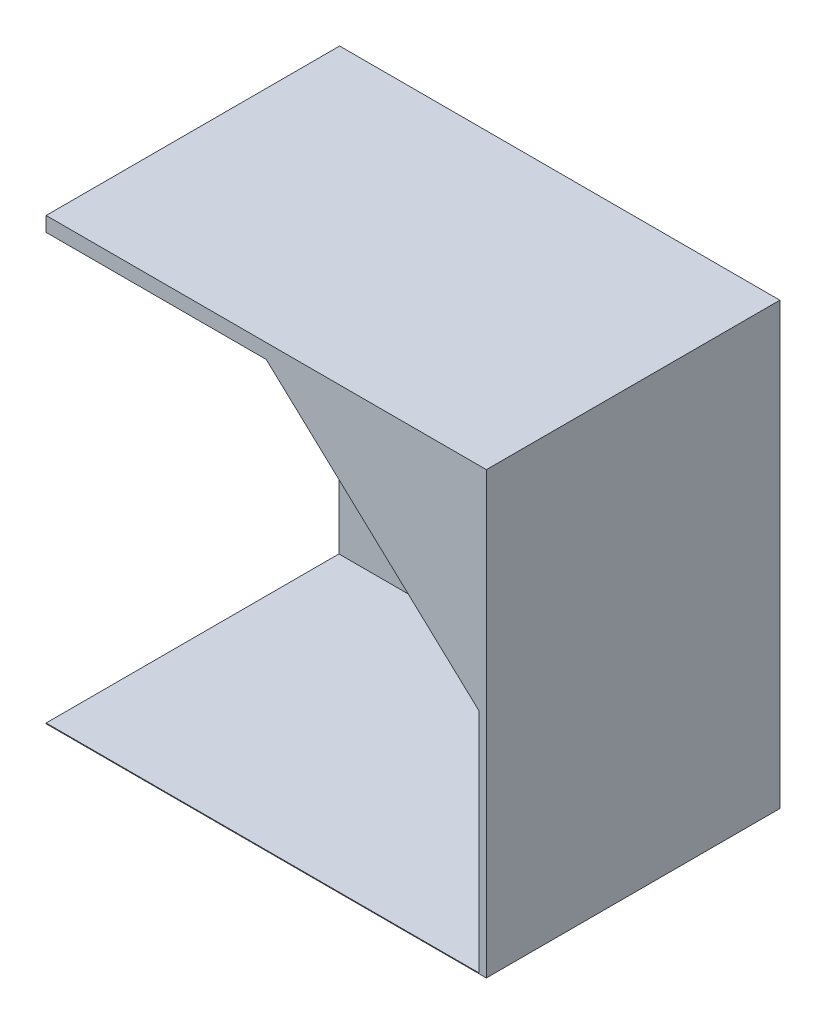
SolidWorks part; units mm, degrees
ref_plane "Front Plane" through (0, 0, 0) normal (0, 0, 1) x (1, 0, 0)
ref_plane "Top Plane" through (0, 0, 0) normal (0, 1, 0) x (1, 0, 0)
ref_plane "Right Plane" through (0, 0, 0) normal (1, 0, 0) x (0, 0, -1)
sketch "Sketch1" plane through (0, 0, 0) normal (0, 0, 1) x (1, 0, 0)
  line L0 (-1599.1508, 0) -> (1757.5573, 0) construction
  line L1 (0, 899.5223) -> (0, -922.1518) construction
  line L3 (1500, -1500) -> (-1500, -1500)
  line L4 (1500, -1500) -> (1500, 1500)
  line L5 (1500, 1500) -> (-1500, 1500)
  line L6 (-1500, -1500) -> (-1500, 1500)
  line L7 (1500, -1500) -> (-1500, 1500) construction
  line L8 (1500, 1500) -> (-1500, -1500) construction
  point P5 (0, 0)
  dimension "D1" = 3000
  dimension "D2" = 3000
extrude "Boss-Extrude1" add sketch "Sketch1" along normal blind 2000
sketch "Sketch2" plane through (0, 0, 2000) normal (0, 0, 1) x (1, 0, 0)
  line L1 (0, 1400) -> (-1500, 1400)
  line L2 (-1500, -1500) -> (1500, -1500) construction
  line L3 (-950, -1495) -> (-1500, -1495)
  line L5 (0, 1400) -> (1450, 51.2327)
  line L6 (1450, 51.2327) -> (1450, -1495)
  line L7 (0, 650.994) -> (0, -1329.3274) construction
  line L8 (-1500, 1500) -> (-1500, -1500) construction
  line L9 (-950, -1495) -> (1450, -1495)
  line L10 (-1500, -1495) -> (-1500, 1400)
  line L11 (1500, -1500) -> (1500, 1500) construction
  line L12 (1500, 1500) -> (-1500, 1500) construction
  dimension "D1" = 50
  dimension "D2" = 100
  dimension "D3" = 5
extrude "Cut-Extrude4" cut sketch "Sketch2" against normal blind 1995 and the other way through all
sketch "Sketch3" plane through (698.1708, 750.5725, 0) normal (-0.6811, -0.7322, 0) x (0.7322, -0.6811, 0)
  line L0 (36.6417, 5) -> (36.6417, 2000) construction
  line L1 (-953.519, 5) -> (1026.8025, 5) construction
  line L2 (1026.8025, 2000) -> (-953.519, 2000) construction
  line L3 (-953.519, 1500) -> (1026.8025, 1500) construction
  line L4 (-953.519, 2000) -> (-953.519, 5) construction
  line L5 (1026.8025, 2000) -> (1026.8025, 5) construction
  line L6 (-953.519, 1000) -> (1026.8025, 1000) construction
  line L7 (-953.519, 500) -> (1026.8025, 500) construction
  circle A0 centre (36.6417, 1500) radius 100
  circle A1 centre (36.6417, 1002.5) radius 100
  circle A2 centre (36.6417, 500) radius 100
  dimension "D1" = 500
  dimension "D2" = 500
  dimension "D3" = 500
  dimension "D4" = 495
extrude "Cut-Extrude5" cut sketch "Sketch3" against normal blind 20
